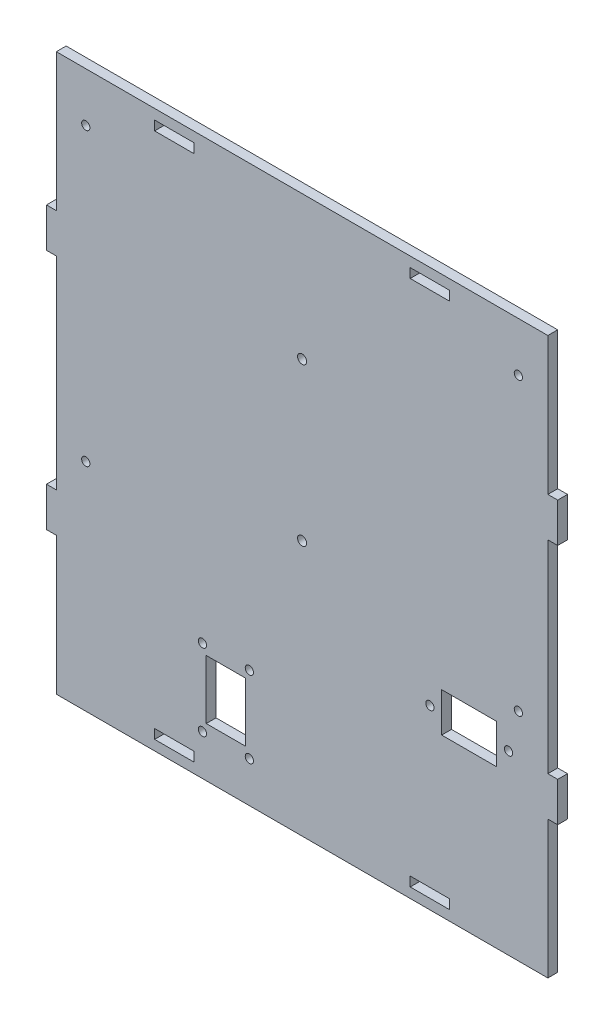
SolidWorks part; units mm, degrees
ref_plane "Front Plane" through (0, 0, 0) normal (0, 0, 1) x (1, 0, 0)
ref_plane "Top Plane" through (0, 0, 0) normal (0, 1, 0) x (1, 0, 0)
ref_plane "Right Plane" through (0, 0, 0) normal (1, 0, 0) x (0, 0, -1)
sketch "Sketch1" plane through (0, 0, 0) normal (0, 0, 1) x (1, 0, 0)
  line L0 (200, 0) -> (250, 0) construction
  line L1 (0, 278) -> (250, 278)
  line L2 (0, 278) -> (0, -5)
  line L3 (0, -5) -> (250, -5)
  line L4 (250, 278) -> (250, -5)
  line L5 (250, 5) -> (250, 0) construction
  line L7 (62, 268) -> (188, 268) construction
  line L8 (50, 0) -> (50, 5) construction
  line L9 (70, 0) -> (70, 5) construction
  line L10 (50, 4.9) -> (70, 4.9)
  line L11 (50, 4.9) -> (50, 0.1)
  line L12 (50, 0.1) -> (70, 0.1)
  line L13 (70, 4.9) -> (70, 0.1)
  line L14 (50, 0) -> (70, 0) construction
  line L15 (180, 0) -> (180, 5) construction
  line L16 (180, 4.9) -> (200, 4.9)
  line L17 (180, 4.9) -> (180, 0.1)
  line L18 (180, 0.1) -> (200, 0.1)
  line L19 (200, 4.9) -> (200, 0.1)
  line L20 (200, 0) -> (200, 5) construction
  line L21 (200, 0) -> (180, 0) construction
  line L22 (0, 5) -> (0, 0) construction
  line L23 (180, 272.9) -> (200, 272.9)
  line L24 (180, 272.9) -> (180, 268.1)
  line L25 (180, 268.1) -> (200, 268.1)
  line L26 (200, 272.9) -> (200, 268.1)
  line L27 (70, 272.9) -> (50, 272.9)
  line L28 (70, 272.9) -> (70, 268.1)
  line L29 (70, 268.1) -> (50, 268.1)
  line L30 (50, 272.9) -> (50, 268.1)
  circle A0 centre (125, 125.1) radius 2.3 construction
  circle A1 centre (125, 205.1) radius 2.3 construction
  circle A2 centre (125, 125.1) radius 2.3
  circle A3 centre (125, 205.1) radius 2.3
  dimension "D1" = 5
  dimension "D2" = 10
  dimension "D3" = 4.8
  dimension "D4" = 0.1
  dimension "D5" = 4.8
  dimension "D6" = 0.1
  dimension "D7" = 4.8
  dimension "D8" = 0.1
  dimension "D9" = 4.8
  dimension "D10" = 0.1
extrude "Boss-Extrude1" add sketch "Sketch1" along normal blind 5
sketch "Sketch2" plane through (0, 0, 5) normal (0, 0, 1) x (1, 0, 0)
  line L0 (0, 278) -> (0, -5) construction
  line L1 (0, 208) -> (-5, 208)
  line L2 (0, 208) -> (0, 188)
  line L3 (0, 188) -> (-5, 188)
  line L4 (-5, 208) -> (-5, 188)
  line L5 (250, -5) -> (250, 278) construction
  line L6 (0, 85) -> (-5, 85)
  line L7 (0, 85) -> (0, 65)
  line L8 (0, 65) -> (-5, 65)
  line L9 (-5, 85) -> (-5, 65)
  line L10 (250, 208) -> (255, 208)
  line L11 (250, 208) -> (250, 188)
  line L12 (250, 188) -> (255, 188)
  line L13 (255, 208) -> (255, 188)
  line L14 (250, 278) -> (0, 278) construction
  line L15 (250, 85) -> (255, 85)
  line L16 (250, 85) -> (250, 65)
  line L17 (250, 65) -> (255, 65)
  line L18 (255, 85) -> (255, 65)
  line L19 (0, -5) -> (250, -5) construction
  dimension "D1" = 5
  dimension "D2" = 20
  dimension "D3" = 70
  dimension "D4" = 70
extrude "Boss-Extrude2" add sketch "Sketch2" against normal up to surface (5 mm away) up to face at (190, 270.5, 0)
sketch "Sketch3" plane through (0, 0, 5) normal (0, 0, 1) x (1, 0, 0)
  line L0 (210, 95) -> (210, 75) construction
  line L1 (196, 95) -> (224, 95)
  line L2 (196, 95) -> (196, 75)
  line L3 (196, 75) -> (224, 75)
  line L4 (224, 95) -> (224, 75)
  line L5 (250, 5) -> (250, 80) construction
  line L6 (0, -5) -> (250, -5) construction
  circle A0 centre (190, 85) radius 2.1
  circle A1 centre (230, 85) radius 2.1
  dimension "D3" = 4.2
  dimension "D4" = 4.2
  dimension "D5" = 40
  dimension "D6" = 20
  dimension "D7" = 10
  dimension "D1" = 28
  dimension "D2" = 20
  dimension "D8" = 40
  dimension "D9" = 80
extrude "Cut-Extrude1" cut sketch "Sketch3" against normal blind 5
sketch "Sketch4" plane through (0, 0, 5) normal (0, 0, 1) x (1, 0, 0)
  line L0 (0, 65) -> (0, -5) construction
  line L1 (76.25, 50.2) -> (96.25, 50.2)
  line L2 (76.25, 50.2) -> (76.25, 20.2)
  line L3 (76.25, 20.2) -> (96.25, 20.2)
  line L4 (96.25, 50.2) -> (96.25, 20.2)
  line L5 (0, -5) -> (250, -5) construction
  dimension "D1" = 20
  dimension "D2" = 30
  dimension "D3" = 76.25
  dimension "D4" = 25.2
extrude "Cut-Extrude2" cut sketch "Sketch4" against normal blind 5
sketch "Sketch5" plane through (0, 0, 5) normal (0, 0, 1) x (1, 0, 0)
  circle A0 centre (98.1863, 15.72) radius 2.1 construction
  circle A1 centre (74.3137, 15.72) radius 2.1 construction
  circle A2 centre (74.3137, 54.68) radius 2.1 construction
  circle A3 centre (98.1863, 54.68) radius 2.1 construction
  circle A4 centre (98.1863, 15.72) radius 2.1
  circle A5 centre (74.3137, 15.72) radius 2.1
  circle A6 centre (74.3137, 54.68) radius 2.1
  circle A7 centre (98.1863, 54.68) radius 2.1
extrude "Cut-Extrude3" cut sketch "Sketch5" against normal through all
sketch "Sketch6" plane through (0, 0, 5) normal (0, 0, 1) x (1, 0, 0)
  line L0 (200, 268) -> (250, 268) construction
  line L1 (250, 208) -> (250, 278) construction
  line L2 (250, -5) -> (250, 278) construction
  line L3 (0, 268) -> (50, 268) construction
  line L4 (0, 258) -> (0, 268) construction
  circle A0 centre (235, 253) radius 2.1
  circle A1 centre (15, 253) radius 2.1
  dimension "D1" = 15
  dimension "D3" = 4.2
  dimension "D4" = 4.2
  dimension "D5" = 15
  dimension "D6" = 15
  dimension "D2" = 15
extrude "Cut-Extrude4" cut sketch "Sketch6" against normal blind 5
sketch "Sketch7" plane through (0, 0, 5) normal (0, 0, 1) x (1, 0, 0)
  line L0 (0, -5) -> (0, 278) construction
  line L1 (0, -5) -> (250, -5) construction
  line L2 (250, 85) -> (250, 188) construction
  circle A0 centre (15, 105) radius 2.1
  circle A1 centre (235, 105) radius 2.1
  dimension "D1" = 4.2
  dimension "D4" = 4.2
  dimension "D5" = 15
  dimension "D6" = 110
  dimension "D2" = 15
  dimension "D3" = 110
extrude "Cut-Extrude5" cut sketch "Sketch7" against normal blind 5
